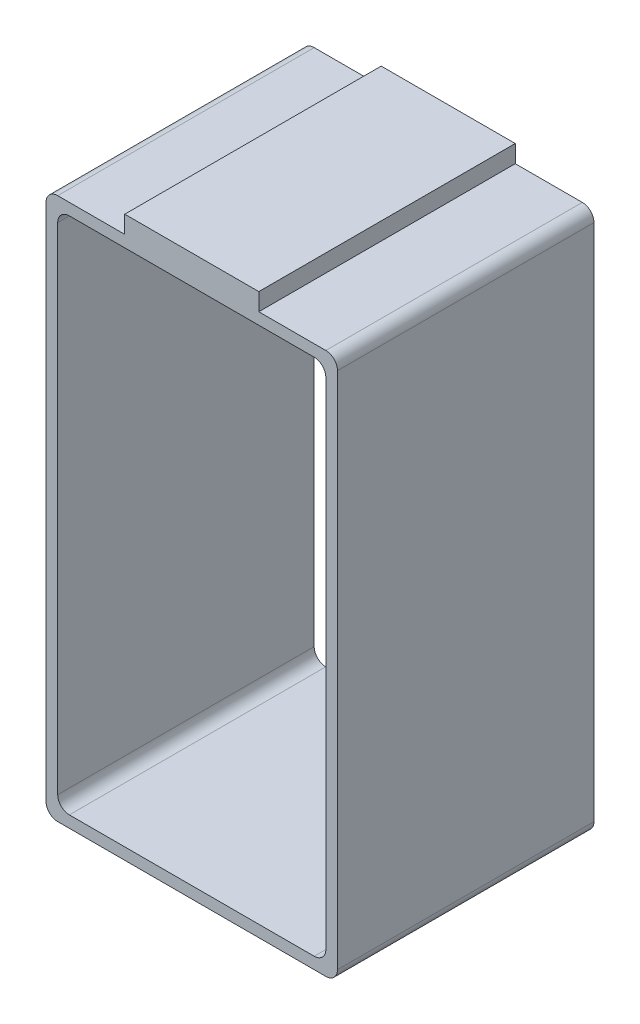
SolidWorks part; units mm, degrees
ref_plane "Front Plane" through (0, 0, 0) normal (0, 0, 1) x (1, 0, 0)
ref_plane "Top Plane" through (0, 0, 0) normal (0, 1, 0) x (1, 0, 0)
ref_plane "Right Plane" through (0, 0, 0) normal (1, 0, 0) x (0, 0, -1)
sketch "Sketch1" plane through (0, 0, 0) normal (0, 0, 1) x (1, 0, 0)
  line L0 (6.75, 1.5) -> (6.75, 0)
  line L1 (1, 0) -> (6.75, 0)
  line L2 (0, -1) -> (0, -45.5)
  line L3 (1, -46.5) -> (24, -46.5)
  line L4 (25, -1) -> (25, -45.5)
  line L5 (6.75, 1.5) -> (18.25, 1.5)
  line L6 (18.25, 0) -> (24, 0)
  line L8 (18.25, 1.5) -> (18.25, 0)
  arc A0 (24, -46.5) -> (25, -45.5) centre (24, -45.5) ccw
  arc A1 (1, -46.5) -> (0, -45.5) centre (1, -45.5) cw
  arc A2 (25, -1) -> (24, 0) centre (24, -1) ccw
  arc A3 (0, -1) -> (1, 0) centre (1, -1) cw
  point P5 (12.5, 0)
  point P6 (12.5, 1.5)
  point P7 (18.25, 1.5)
  point P14 (25, -46.5)
  point P19 (25, 0)
  point P22 (0, 0)
  dimension "D5" = 1
  dimension "D1" = 25
  dimension "D2" = 46.5
  dimension "D3" = 1.5
  dimension "D4" = 5.75
extrude "Boss-Extrude1" add sketch "Sketch1" along normal blind 22
sketch "Sketch2" plane through (0, 0, 22) normal (0, 0, 1) x (1, 0, 0)
  line L1 (2, -1) -> (23, -1)
  line L5 (24, -2) -> (24, -44.5)
  line L6 (2, -45.5) -> (23, -45.5)
  line L7 (1, -2) -> (1, -44.5)
  arc A0 (2, -45.5) -> (1, -44.5) centre (2, -44.5) cw
  arc A1 (23, -45.5) -> (24, -44.5) centre (23, -44.5) ccw
  arc A2 (24, -2) -> (23, -1) centre (23, -2) ccw
  arc A3 (1, -2) -> (2, -1) centre (2, -2) cw
  point P19 (0, 0)
  dimension "D1" = 1
extrude "Cut-Extrude1" cut sketch "Sketch2" against normal blind 22
